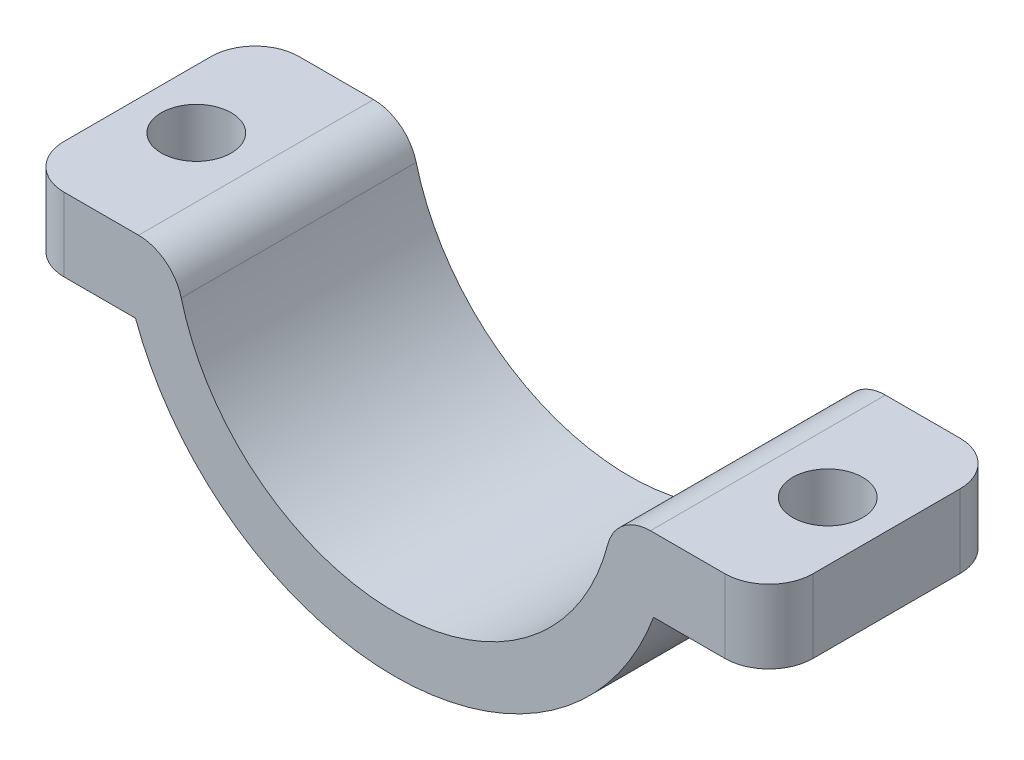
SolidWorks part; units mm, degrees
ref_plane "Alzado" through (0, 0, 0) normal (0, 0, 1) x (1, 0, 0)
ref_plane "Planta" through (0, 0, 0) normal (0, 1, 0) x (1, 0, 0)
ref_plane "Vista lateral" through (0, 0, 0) normal (1, 0, 0) x (0, 0, -1)
sketch "Croquis1" plane through (0, 0, 0) normal (0, 0, 1) x (1, 0, 0)
  line L0 (29.1365, 0) -> (-34.4299, 0) construction
  line L1 (-11.5, -1.5) -> (-25.5, -1.5)
  line L2 (-11.5, -1.5) -> (-11.5, -6.5)
  line L3 (-11.5, -6.5) -> (-25.5, -6.5)
  line L4 (-25.5, -1.5) -> (-25.5, -6.5)
  line L9 (0, 11.3797) -> (0, -23.4351) construction
  line L10 (11.5, -6.5) -> (25.5, -6.5)
  line L11 (-23.8813, -5.5) -> (-19.1187, -5.5) construction
  line L12 (-23.8813, -5.5) -> (-23.8813, -2.5) construction
  line L13 (-23.8813, -2.5) -> (-19.1187, -2.5) construction
  line L14 (-19.1187, -5.5) -> (-19.1187, -2.5) construction
  line L15 (-23.8813, -5.5) -> (-19.1187, -2.5) construction
  line L16 (-23.8813, -2.5) -> (-19.1187, -5.5) construction
  line L17 (25.5, -1.5) -> (25.5, -6.5)
  line L18 (11.5, -1.5) -> (25.5, -1.5)
  line L19 (11.5, -1.5) -> (11.5, -6.5)
  circle A0 centre (0, 0) radius 15
  circle A1 centre (0, 0) radius 18.8
  point P13 (-21.5, -4)
  dimension "D2" = 30
  dimension "D1" = 1.5
  dimension "D3" = 25.5
  dimension "D4" = 14
  dimension "D5" = 5
  dimension "D7" = 4.7625
  dimension "D8" = 4
  dimension "D9" = 2.5
  dimension "D10" = 3
  dimension "D6" = 3.8
extrude "Saliente-Extruir1" add sketch "Croquis1" along normal mid plane 16 contours A1 L10 L17 L18 | L10 A1 L18 A0 | L3 A1 L10 A0 | L1 A1 L3 A0 | A1 L1 L4 L3
sketch "Croquis2" plane through (0, -1.5, 0) normal (0, 1, 0) x (1, 0, 0)
  line L0 (33.8639, 0) -> (-39.883, 0) construction
  line L1 (0, 13.5336) -> (0, -15.2197) construction
  line L2 (-25.5, -8) -> (-25.5, 8) construction
  circle A0 centre (-21.5, 0) radius 2.3813
  circle A1 centre (21.5, 0) radius 2.3813
  dimension "D2" = 4.7625
  dimension "D1" = 4
extrude "Cortar-Extruir1" cut sketch "Croquis2" against normal blind 16
fillet "Redondeo1" radius 3 6 edges at (14.9248, -1.5, 0) (-14.9248, -1.5, 0) (-25.5, -4, -8) (-25.5, -4, 8) (25.5, -4, -8) (25.5, -4, 8)
